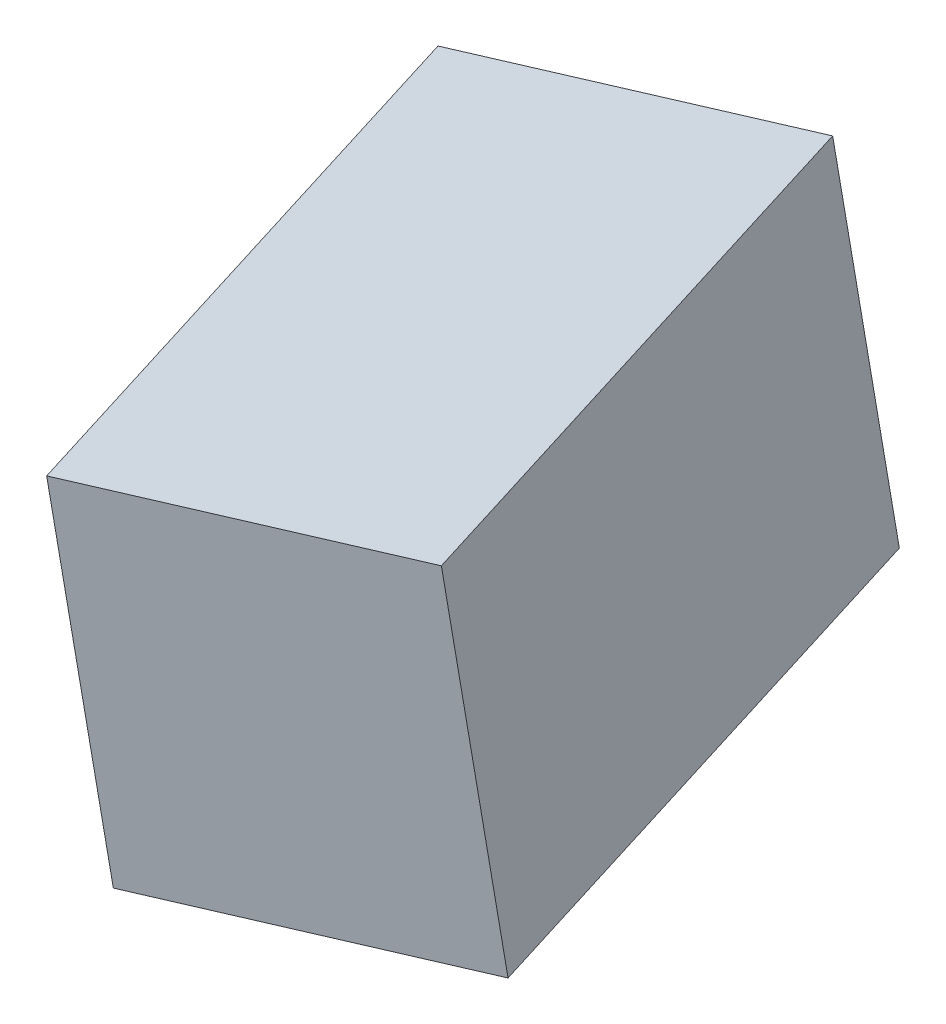
SolidWorks part; units mm, degrees
ref_plane "前视基准面" through (0, 0, 0) normal (0, 0, 1) x (1, 0, 0)
ref_plane "上视基准面" through (0, 0, 0) normal (0, 1, 0) x (1, 0, 0)
ref_plane "右视基准面" through (0, 0, 0) normal (1, 0, 0) x (0, 0, -1)
other "Configuration Table"
sketch "草图2" plane through (-1970.0344, 250.6885, 166.1461) normal (0.9612, 0.1167, -0.2498) x (0.0974, -0.9913, -0.0885)
  line L1 (-90.2874, 65.5199) -> (-145.2874, 65.5199)
  line L2 (-90.2874, 65.5199) -> (-90.2874, -19.4801)
  line L3 (-90.2874, -19.4801) -> (-145.2874, -19.4801)
  line L4 (-145.2874, 65.5199) -> (-145.2874, -19.4801)
  dimension "D1" = 85
  dimension "D2" = 55
extrude "凸台-拉伸1" add sketch "草图2" along normal blind 50
